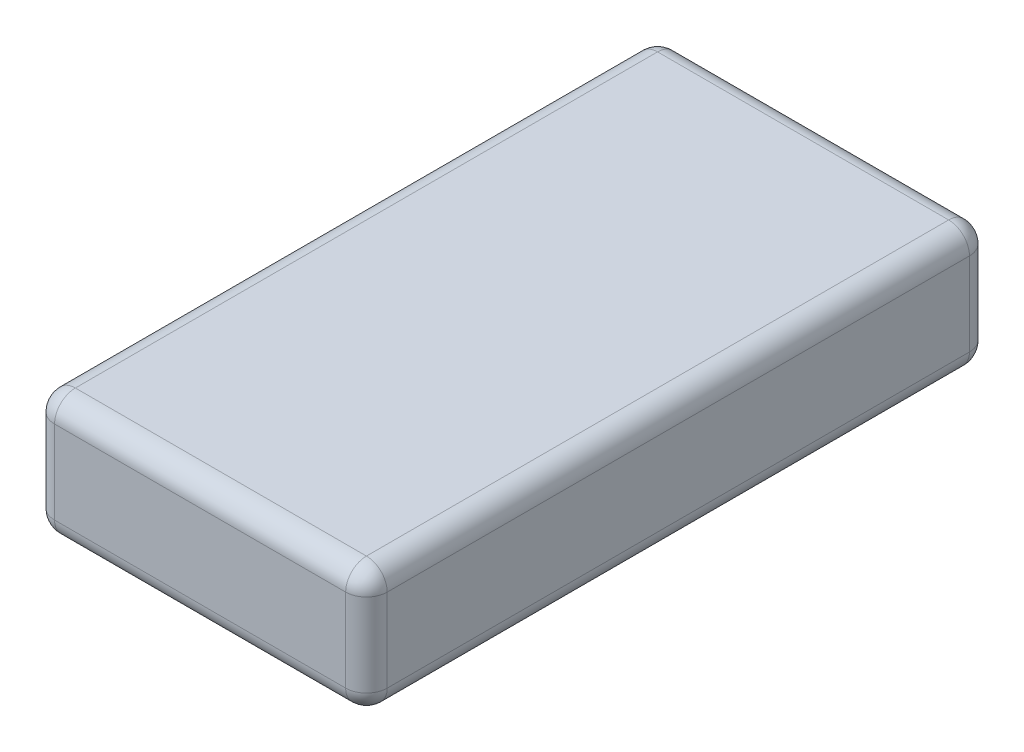
SolidWorks part; units mm, degrees
ref_plane "前视基准面" through (0, 0, 0) normal (0, 0, 1) x (1, 0, 0)
ref_plane "上视基准面" through (0, 0, 0) normal (0, 1, 0) x (1, 0, 0)
ref_plane "右视基准面" through (0, 0, 0) normal (1, 0, 0) x (0, 0, -1)
sketch "草图1" plane through (0, 0, 0) normal (0, 1, 0) x (1, 0, 0)
  line L1 (-16, 30) -> (16, 30)
  line L2 (16, 30) -> (16, -30)
  line L4 (-16, -30) -> (16, -30)
  line L5 (-16, 30) -> (-16, -30)
  point P7 (0, -30)
extrude "凸台-拉伸1" add sketch "草图1" along normal blind 12
fillet "圆角1" radius 2 12 edges at (-16, 6, 30) (16, 6, 30) (16, 6, -30) (-16, 6, -30) (0, 12, -30) (16, 12, 0) (0, 12, 30) (-16, 12, 0) (0, 0, 30) (16, 0, 0) (0, 0, -30) (-16, 0, 0)
